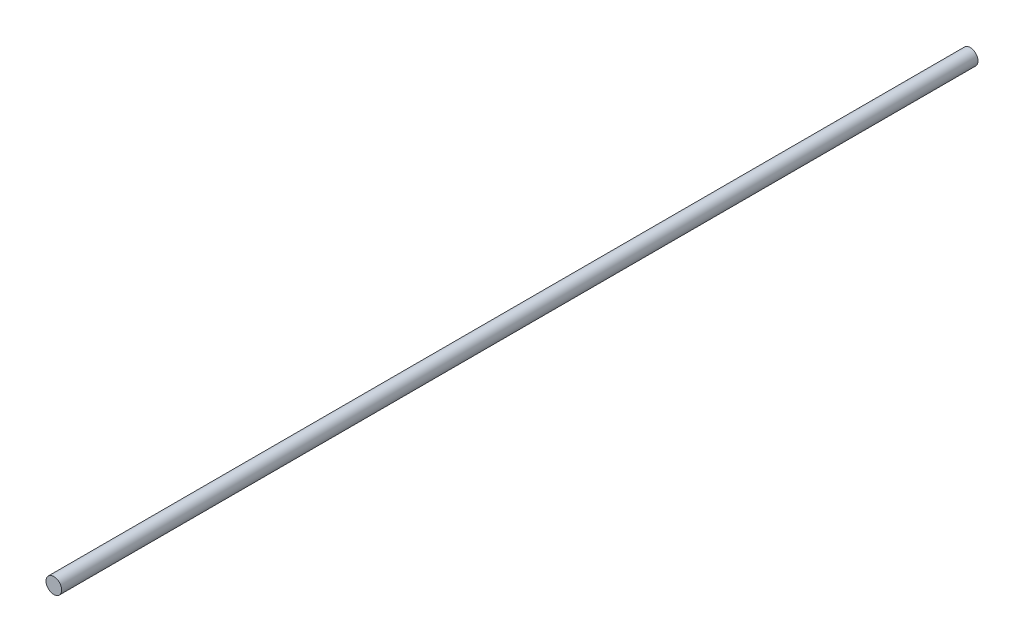
SolidWorks part; units mm, degrees
ref_plane "Front Plane" through (0, 0, 0) normal (0, 0, 1) x (1, 0, 0)
ref_plane "Top Plane" through (0, 0, 0) normal (0, 1, 0) x (1, 0, 0)
ref_plane "Right Plane" through (0, 0, 0) normal (1, 0, 0) x (0, 0, -1)
sketch "Sketch1" plane through (0, 0, 0) normal (0, 0, 1) x (1, 0, 0)
  circle A0 centre (0, 0) radius 4.7625
extrude "Boss-Extrude1" add sketch "Sketch1" along normal blind 558.8
